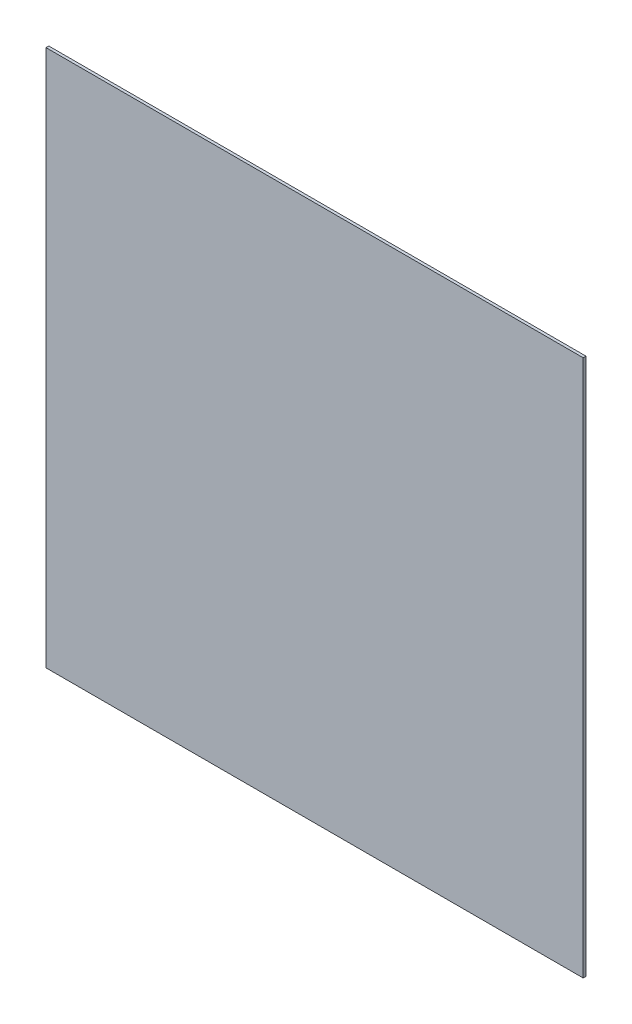
SolidWorks part; units mm, degrees
ref_plane "Front Plane" through (0, 0, 0) normal (0, 0, 1) x (1, 0, 0)
ref_plane "Top Plane" through (0, 0, 0) normal (0, 1, 0) x (1, 0, 0)
ref_plane "Right Plane" through (0, 0, 0) normal (1, 0, 0) x (0, 0, -1)
sketch "Sketch1" plane through (0, 0, 0) normal (0, 0, 1) x (1, 0, 0)
  line L0 (0, 0) -> (0, 609.6)
  line L1 (0, 609.6) -> (609.6, 609.6)
  line L2 (609.6, 609.6) -> (609.6, 0)
  line L3 (609.6, 0) -> (0, 0)
  point P3 (0, 0)
  dimension "D1" = 609.6
  dimension "D2" = 609.6
extrude "Boss-Extrude1" add sketch "Sketch1" along normal blind 3.175
